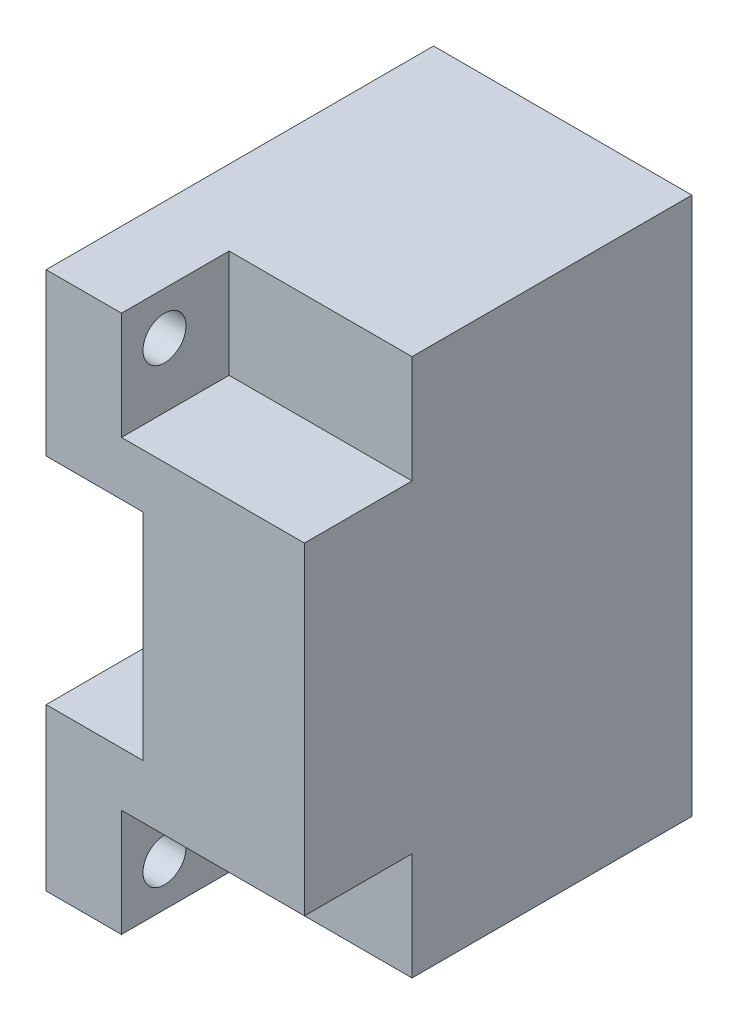
SolidWorks part; units mm, degrees
ref_plane "前视基准面" through (0, 0, 0) normal (0, 0, 1) x (1, 0, 0)
ref_plane "上视基准面" through (0, 0, 0) normal (0, 1, 0) x (1, 0, 0)
ref_plane "右视基准面" through (0, 0, 0) normal (1, 0, 0) x (0, 0, -1)
sketch "草图1" plane through (0, 0, 0) normal (0, 0, 1) x (1, 0, 0)
  line L1 (-12.5, -12.5) -> (12.5, -12.5)
  line L2 (-12.5, -12.5) -> (-12.5, 12.5)
  line L3 (-12.5, 12.5) -> (12.5, 12.5)
  line L4 (12.5, -12.5) -> (12.5, 12.5)
  line L5 (-12.5, -12.5) -> (12.5, 12.5) construction
  line L6 (-12.5, 12.5) -> (12.5, -12.5) construction
  point P0 (0, 0)
  dimension "D1" = 25
  dimension "D2" = 25
extrude "凸台-拉伸1" add sketch "草图1" along normal blind 10
sketch "草图2" plane through (0, 0, 10) normal (0, 0, 1) x (1, 0, 0)
  circle A0 centre (0, 0) radius 10
  dimension "D1" = 20
extrude "切除-拉伸1" cut sketch "草图2" against normal offset from surface (7 mm away) 3 up to face at (0, 0, 0)
sketch "草图3" plane through (0, 0, 3) normal (0, 0, 1) x (1, 0, 0)
  circle A0 centre (0, 0) radius 4.5
  dimension "D1" = 9
extrude "切除-拉伸2" cut sketch "草图3" against normal through all
sketch "草图4" plane through (0, 0, 3) normal (0, 0, 1) x (1, 0, 0)
  line L0 (-12.5, 12.5) -> (0, 0) construction
  circle A0 centre (-4.9497, 4.9497) radius 2
  dimension "D1" = 4
  dimension "D2" = 7
extrude "切除-拉伸4" cut sketch "草图4" against normal through all
pattern_circular "阵列(圆周)1" count 4 over 360 about axis through (0, 0, 0) along (0, 0, 1) of "切除-拉伸4"
sketch "草图5" plane through (0, 0, 10) normal (0, 0, 1) x (1, 0, 0)
  line L0 (-12.5, -12.5) -> (12.5, -12.5) construction
  line L1 (12.5, -12.5) -> (12.5, 12.5) construction
  line L2 (12.5, 12.5) -> (-12.5, 12.5) construction
  line L3 (-12.5, 12.5) -> (-12.5, -12.5) construction
  line L4 (-12.5, -12.5) -> (12.5, -12.5)
  line L5 (12.5, -12.5) -> (12.5, 12.5)
  line L6 (12.5, 12.5) -> (-12.5, 12.5)
  line L7 (-12.5, 12.5) -> (-12.5, -12.5)
extrude "凸台-拉伸2" add sketch "草图5" along normal blind 8
sketch "草图6" plane through (0, 0, 18) normal (0, 0, 1) x (1, 0, 0)
  line L1 (-5, -5) -> (5, -5)
  line L2 (-5, -5) -> (-5, 5)
  line L3 (-5, 5) -> (5, 5)
  line L4 (5, -5) -> (5, 5)
  line L5 (-5, -5) -> (5, 5) construction
  line L6 (-5, 5) -> (5, -5) construction
  point P0 (0, 0)
  dimension "D1" = 10
  dimension "D2" = 10
extrude "切除-拉伸5" cut sketch "草图6" against normal blind 8
sketch "草图7" plane through (0, 0, 18) normal (0, 0, 1) x (1, 0, 0)
  line L0 (-12.5, -12.5) -> (12.5, -12.5) construction
  line L1 (12.5, -12.5) -> (12.5, 12.5) construction
  line L2 (12.5, 12.5) -> (-12.5, 12.5) construction
  line L3 (-12.5, 12.5) -> (-12.5, -12.5) construction
  line L4 (-12.5, -12.5) -> (12.5, -12.5)
  line L5 (12.5, -12.5) -> (12.5, 12.5)
  line L6 (12.5, 12.5) -> (-12.5, 12.5)
  line L7 (-12.5, 12.5) -> (-12.5, -12.5)
  line L8 (5, 5) -> (-5, 5) construction
  line L9 (-9, -9) -> (9, -9)
  line L10 (-9, -9) -> (-9, 9)
  line L11 (-9, 9) -> (9, 9)
  line L12 (9, -9) -> (9, 9)
  line L13 (-9, -9) -> (9, 9) construction
  line L14 (-9, 9) -> (9, -9) construction
  line L15 (5, -5) -> (5, 5) construction
  line L17 (-12.5, -12.5) -> (12.5, -12.5)
  line L18 (-12.5, -12.5) -> (-12.5, 12.5)
  line L19 (-12.5, 12.5) -> (12.5, 12.5)
  line L20 (12.5, -12.5) -> (12.5, 12.5)
  line L21 (-12.5, -12.5) -> (12.5, 12.5) construction
  line L22 (-12.5, 12.5) -> (12.5, -12.5) construction
  point P2 (0, 0)
  point P14 (0, 0)
  dimension "D1" = 4
  dimension "D2" = 4
sketch "草图8" plane through (0, -12.5, 0) normal (0, -1, 0) x (1, 0, 0)
  line L1 (0, 0) -> (17.4478, 0)
  line L2 (0, 0) -> (0, 20.9451)
  line L3 (0, 20.9451) -> (17.4478, 20.9451)
  line L4 (17.4478, 0) -> (17.4478, 20.9451)
extrude "切除-拉伸8" cut sketch "草图8" against normal through all
sketch "草图12" plane through (0, 0, 0) normal (1, 0, 0) x (0, 0, -1)
  line L1 (-18, -12.5) -> (-13, -12.5)
  line L2 (-18, -12.5) -> (-18, -7.5)
  line L3 (-18, -7.5) -> (-13, -7.5)
  line L4 (-13, -12.5) -> (-13, -7.5)
  dimension "D1" = 5
  dimension "D2" = 5
extrude "切除-拉伸9" cut sketch "草图12" against normal through all from offset 4 offset against normal yes
mirror "镜向1" about plane through (0, 0, 0) normal (0, 1, 0) of "切除-拉伸9"
sketch "草图13" plane through (-4, 0, 0) normal (-1, 0, 0) x (0, 0, 1)
  line L0 (18, -12.5) -> (13, -12.5) construction
  line L1 (18, -12.5) -> (18, 12.5) construction
  circle A0 centre (16, -10.5) radius 1
  dimension "D1" = 2
  dimension "D2" = 2
  dimension "D3" = 2
extrude "切除-拉伸10" cut sketch "草图13" against normal through all
mirror "镜向2" about plane through (0, 0, 0) normal (0, 1, 0) of "切除-拉伸10"
mirror "镜向3" about plane through (0, 12.5, 0) normal (-1, 0, 0) of bodies 115
sketch "草图14" plane through (0, -12.5, 0) normal (0, -1, 0) x (1, 0, 0)
  line L0 (-12.5, 0) -> (12.5, 0) construction
  line L1 (0.5, 0) -> (-16.3818, 0)
  line L2 (0.5, 0) -> (0.5, 21.4474)
  line L3 (0.5, 21.4474) -> (-16.3818, 21.4474)
  line L4 (-16.3818, 0) -> (-16.3818, 21.4474)
  dimension "D1" = 0.5
extrude "切除-拉伸11" cut sketch "草图14" against normal through all
